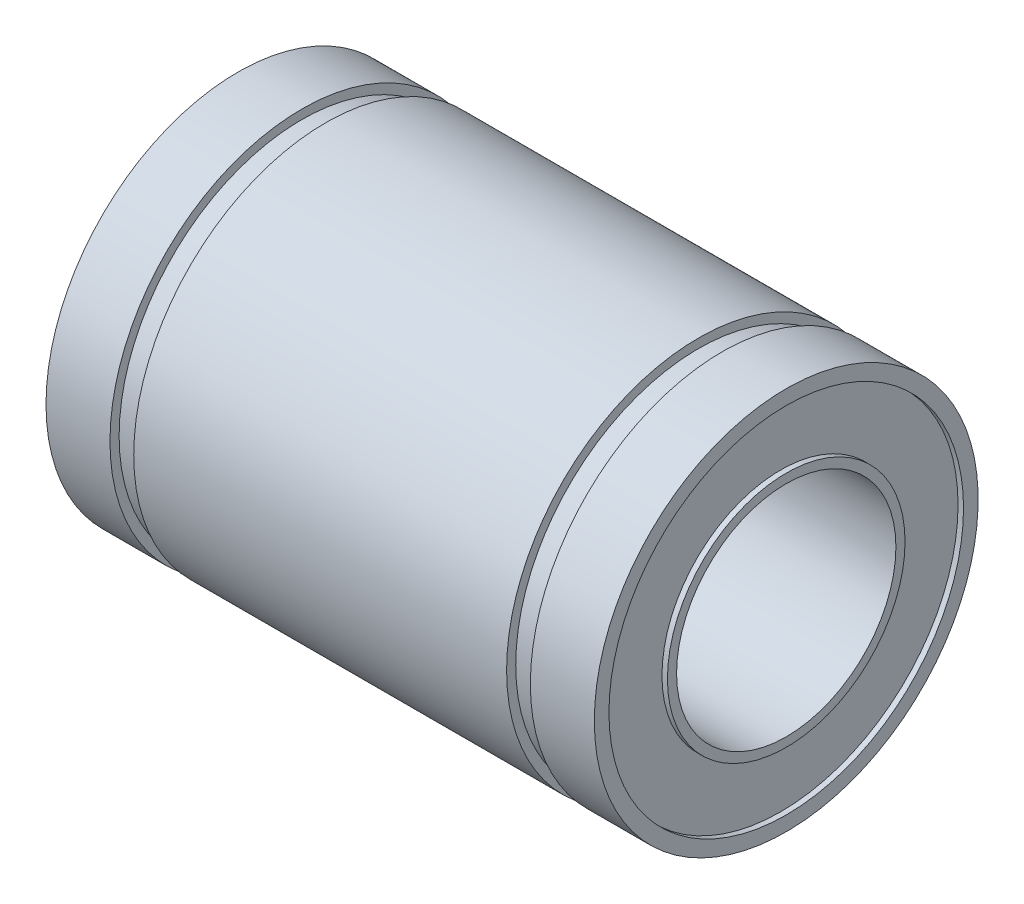
SolidWorks part; units mm, degrees
material "Plain Carbon Steel"
ref_plane "Front Plane" through (0, 0, 0) normal (0, 0, 1) x (1, 0, 0)
ref_plane "Top Plane" through (0, 0, 0) normal (0, 1, 0) x (1, 0, 0)
ref_plane "Right Plane" through (0, 0, 0) normal (1, 0, 0) x (0, 0, -1)
sketch "Sketch1" plane through (0, 0, 0) normal (0, 0, 1) x (1, 0, 0)
  line L0 (-15, 0) -> (15, 0) construction
  line L1 (-15, 6) -> (15, 6)
  line L2 (-15, 6) -> (-15, 6.5)
  line L3 (-15, 10.5) -> (-11.5, 10.5)
  line L4 (15, 6) -> (15, 6.5)
  line L5 (11.5, 10.5) -> (15, 10.5)
  line L6 (-15, 9.7) -> (-14.7, 9.7)
  line L7 (0, 0) -> (0, 1.809) construction
  line L8 (-15, 6.5) -> (-14.7, 6.5)
  line L9 (-14.7, 9.7) -> (-14.7, 6.5)
  line L10 (-15, 9.7) -> (-15, 10.5)
  line L11 (-11.5, 10.5) -> (-11.5, 10)
  line L12 (-11.5, 10) -> (-10.2, 10)
  line L13 (-10.2, 10.5) -> (-10.2, 10)
  line L14 (-10.2, 10.5) -> (10.2, 10.5)
  line L15 (11.5, 10.5) -> (11.5, 10)
  line L16 (11.5, 10) -> (10.2, 10)
  line L17 (10.2, 10.5) -> (10.2, 10)
  line L18 (14.7, 9.7) -> (14.7, 6.5)
  line L19 (15, 6.5) -> (14.7, 6.5)
  line L20 (15, 9.7) -> (14.7, 9.7)
  line L21 (15, 9.7) -> (15, 10.5)
  point P21 (15, 10.5)
  point P24 (-15, 10.5)
  dimension "D1" = 12
  dimension "D2" = 21
  dimension "D3" = 30
  dimension "D4" = 0.5
  dimension "D5" = 0.3
  dimension "D6" = 0.8
  dimension "D7" = 23
  dimension "D8" = 1.3
  dimension "D9" = 20
revolve "Revolve1" add sketch "Sketch1" angle 360 about L0
